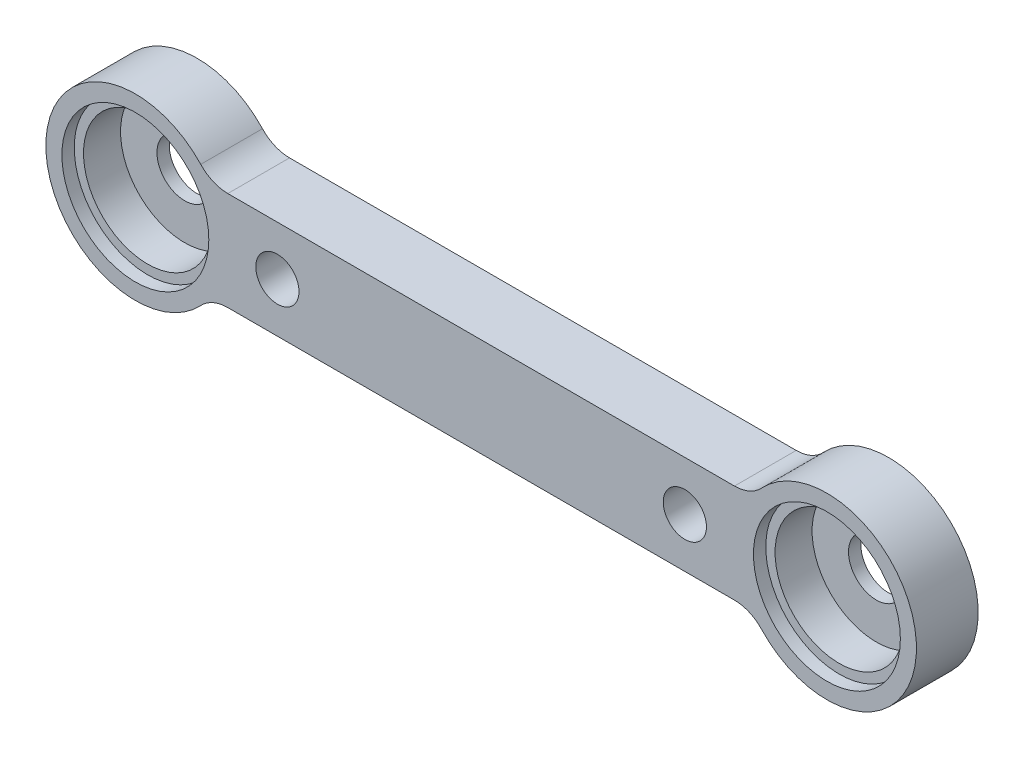
SolidWorks part; units mm, degrees
ref_plane "Front Plane" through (0, 0, 0) normal (0, 0, 1) x (1, 0, 0)
ref_plane "Top Plane" through (0, 0, 0) normal (0, 1, 0) x (1, 0, 0)
ref_plane "Right Plane" through (0, 0, 0) normal (1, 0, 0) x (0, 0, -1)
sketch "Sketch1" plane through (0, 0, 0) normal (0, 0, 1) x (1, 0, 0)
  line L0 (-68.7583, 0) -> (-12.7483, 0) construction
  line L1 (-68.7583, 4) -> (-12.7483, 4)
  line L2 (-68.7583, -4) -> (-12.7483, -4)
  line L3 (-40.7533, 24.4745) -> (-40.7533, -26.4527) construction
  line L4 (-57.2533, 11.294) -> (-57.2533, -11.3824) construction
  line L5 (-24.2533, 11.294) -> (-24.2533, -11.3824) construction
  arc A0 (-68.7583, 4) -> (-68.7583, -4) centre (-68.7583, 0) ccw
  arc A1 (-12.7483, -4) -> (-12.7483, 4) centre (-12.7483, 0) ccw
  circle A5 centre (-57.2533, 0) radius 1.75
  circle A6 centre (-24.2533, 0) radius 1.75
  point P3 (-40.7533, 0)
  dimension "D2" = 3.5
  dimension "D5" = 16.5
  dimension "D1" = 56.01
  dimension "D4" = 8
extrude "Boss-Extrude1" add sketch "Sketch1" along normal blind 5
sketch "Sketch2" plane through (0, 0, 0) normal (0, 0, -1) x (-1, 0, 0)
  line L0 (40.7533, 21.3559) -> (40.7533, -25.0317) construction
  line L1 (-42.2604, 0) -> (84.0743, 0) construction
  line L2 (68.7583, 4) -> (68.7583, -11.3535) construction
  line L3 (12.7483, 4) -> (12.7483, -11.3535) construction
  circle A4 centre (68.7583, 0) radius 7.25
  circle A5 centre (12.7483, 0) radius 7.25
  dimension "D1" = 28.005
extrude "Boss-Extrude2" add sketch "Sketch2" against normal blind 5
sketch "Sketch5" plane through (0, 0, 5) normal (0, 0, 1) x (1, 0, 0)
  circle A0 centre (-68.7583, 0) radius 5.95
  circle A2 centre (-12.7483, 0) radius 5.95
  dimension "D1" = 11.9
  dimension "D2" = 11.9
extrude "Cut-Extrude2" cut sketch "Sketch5" against normal blind 1
sketch "Sketch6" plane through (0, 0, 0) normal (0, 0, -1) x (-1, 0, 0)
  line L0 (-42.0515, 0) -> (78.0782, 0) construction
  line L1 (40.7533, 32.5519) -> (40.7533, -29.3799) construction
  line L2 (12.7483, 15.7982) -> (12.7483, -20.3137) construction
  line L3 (68.7583, 15.7982) -> (68.7583, -20.3137) construction
  circle A0 centre (12.7483, 0) radius 2.25
  circle A2 centre (68.7583, 0) radius 2.25
  dimension "D1" = 28.005
extrude "Cut-Extrude3" cut sketch "Sketch6" against normal blind 4
fillet "Fillet1" radius 3 4 edges at (-18.795, 4, 2.5) (-18.795, -4, 2.5) (-62.7116, -4, 2.5) (-62.7116, 4, 2.5)
sketch "Sketch7" plane through (0, 0, 4) normal (0, 0, 1) x (1, 0, 0)
  circle A0 centre (-68.7583, 0) radius 5.2
  circle A2 centre (-12.7483, 0) radius 5.2
  dimension "D1" = 10.4
  dimension "D2" = 10.4
extrude "Cut-Extrude4" cut sketch "Sketch7" against normal blind 3
